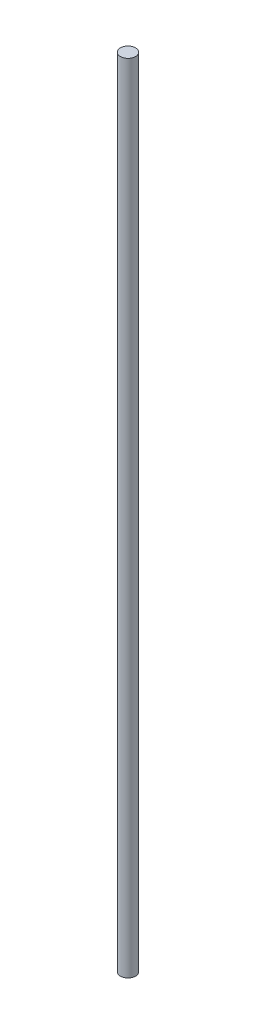
SolidWorks part; units mm, degrees
material "1060 Alloy"
ref_plane "Front Plane" through (0, 0, 0) normal (0, 0, 1) x (1, 0, 0)
ref_plane "Top Plane" through (0, 0, 0) normal (0, 1, 0) x (1, 0, 0)
ref_plane "Right Plane" through (0, 0, 0) normal (1, 0, 0) x (0, 0, -1)
sketch "Sketch1" plane through (0, 0, 0) normal (0, 1, 0) x (1, 0, 0)
  circle A0 centre (0, 0) radius 4.7625
  dimension "D1" = 9.525
extrude "Boss-Extrude1" add sketch "Sketch1" along normal blind 500
